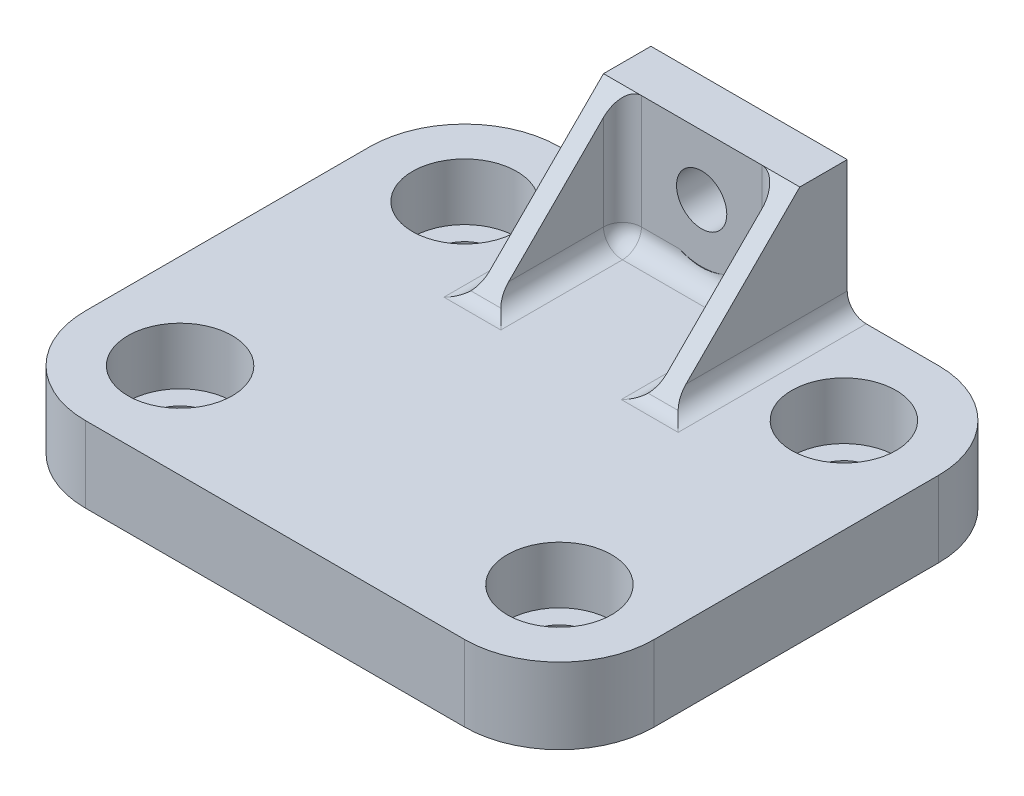
SolidWorks part; units mm, degrees
ref_plane "Front" through (0, 0, 0) normal (0, 0, 1) x (1, 0, 0)
ref_plane "Top" through (0, 0, 0) normal (0, 1, 0) x (1, 0, 0)
ref_plane "Right" through (0, 0, 0) normal (1, 0, 0) x (0, 0, -1)
sketch "Sketch1" plane through (0, 0, 0) normal (0, 1, 0) x (1, 0, 0)
  line L1 (-30, -25) -> (30, -25)
  line L2 (-30, -25) -> (-30, 25)
  line L3 (-30, 25) -> (30, 25)
  line L4 (30, -25) -> (30, 25)
  line L5 (-30, -25) -> (30, 25) construction
  line L6 (-30, 25) -> (30, -25) construction
  line L7 (-20, -15) -> (20, -15) construction
  line L8 (-20, -15) -> (-20, 15) construction
  line L9 (-20, 15) -> (20, 15) construction
  line L10 (20, -15) -> (20, 15) construction
  line L11 (-20, -15) -> (20, 15) construction
  line L12 (-20, 15) -> (20, -15) construction
  point P0 (0, 0)
  point P5 (0, 0)
  dimension "D1" = 30
  dimension "D2" = 40
  dimension "D3" = 60
  dimension "D4" = 50
extrude "Boss-Extrude1" add sketch "Sketch1" along normal blind 8
fillet "Fillet1" radius 10 4 edges at (-30, 4, 25) (-30, 4, -25) (30, 4, -25) (30, 4, 25)
hole_wizard "CBORE for M6 SHCS1" positions "Sketch2" profile "Sketch3" counterbore size "M6" standard "ANSI Metric"
sketch "Sketch2" plane through (0, 8, 0) normal (0, 1, 0) x (1, 0, 0)
  point P0 (-20, 15)
  point P3 (-20, -15)
  point P6 (20, -15)
  point P9 (20, 15)
sketch "Sketch3" plane through (-20, 8, -15) normal (1, 0, 0) x (0, 0, 1)
  line L0 (0, 0) -> (0, 12.0828)
  line L1 (0, 12.0828) -> (3.3, 10.1)
  line L2 (3.3, 10.1) -> (3.3, 6)
  line L3 (3.3, 6) -> (5.5, 6)
  line L4 (5.5, 6) -> (5.5, 0)
  line L5 (5.5, 0) -> (0, 0)
  line L10 (0, 12.0828) -> (-3.3, 10.1) construction
  line L11 (0, -6.35) -> (0, 107.95) construction
  dimension "Hole Dia." = 6.6
  dimension "Hole Depth" = 10.1
  dimension "C'Bore Dia." = 11
  dimension "C'Bore Depth" = 6
  dimension "Drill Angle" = 118
sketch "Sketch4" plane through (0, 0, -25) normal (0, 0, -1) x (-1, 0, 0)
  line L0 (-8.35, 8) -> (-8.35, 22)
  line L1 (-20, 8) -> (20, 8) construction
  line L2 (-8.35, 22) -> (8.35, 22)
  line L3 (8.35, 22) -> (8.35, 8)
  line L4 (0, 0) -> (0, 15.65) construction
  line L5 (-20, 0) -> (20, 0) construction
  line L6 (0, 15.65) -> (0, 22) construction
  line L7 (-8.35, 8) -> (8.35, 8)
  dimension "D1" = 14
  dimension "D2" = 16.7
  dimension "D3" = 6.35
extrude "Boss-Extrude2" add sketch "Sketch4" against normal blind 5 contours L0 L2 L3 L7
hole_wizard "M5 Clearance Hole1" positions "Sketch5" profile "Sketch6" hole size "M5" standard "ANSI Metric"
sketch "Sketch5" plane through (0, 0, -20) normal (0, 0, 1) x (1, 0, 0)
  point P0 (0, 15.65)
sketch "Sketch6" plane through (0, 15.65, -20) normal (1, 0, 0) x (0, -1, 0)
  line L0 (0, 0) -> (0, 11.5923)
  line L1 (0, 11.5923) -> (2.65, 10)
  line L2 (2.65, 10) -> (2.65, 0)
  line L5 (2.65, 0) -> (0, 0)
  line L10 (0, 11.5923) -> (-2.65, 10) construction
  line L11 (0, -6.35) -> (0, 107.95) construction
  dimension "Hole Dia." = 5.3
  dimension "Hole Depth" = 10
  dimension "Drill Angle" = 118
sketch "Sketch7" plane through (8.35, 0, 0) normal (1, 0, 0) x (0, 0, -1)
  line L0 (20, 22) -> (6, 8)
  line L1 (6, 8) -> (25, 8)
  line L2 (25, 8) -> (25, 22)
  line L3 (25, 22) -> (20, 22)
  dimension "D1" = 45
extrude "Boss-Extrude3" add sketch "Sketch7" along normal blind 2
mirror "Mirror1" about plane through (0, 0, 0) normal (1, 0, 0) of "Boss-Extrude3"
fillet "Fillet2" radius 2 9 edges at (0, 8, -20) (-8.35, 15, -20) (8.35, 15, -20) (8.35, 8, -13) (-8.35, 8, -13) (10.35, 8, -15.5) (-10.35, 8, -15.5) (9.35, 8, -6) (-9.35, 8, -6)
sketch "Sketch8" plane through (0, 0, -20) normal (0, 0, 1) x (1, 0, 0)
  circle A0 centre (0, 15.65) radius 6.12
  dimension "D1" = 12.24
extrude "Cut-Extrude1" cut sketch "Sketch8" along normal through all
